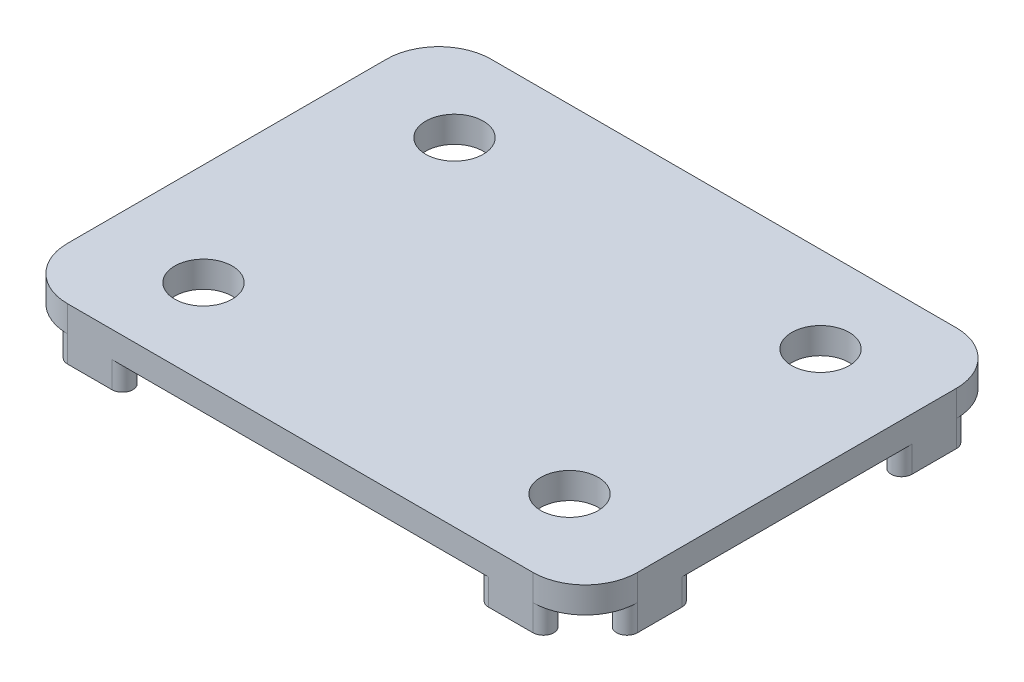
SolidWorks part; units mm, degrees
material "ABS"
ref_plane "Front Plane" through (0, 0, 0) normal (0, 0, 1) x (1, 0, 0)
ref_plane "Top Plane" through (0, 0, 0) normal (0, 1, 0) x (1, 0, 0)
ref_plane "Right Plane" through (0, 0, 0) normal (1, 0, 0) x (0, 0, -1)
sketch "Sketch1" plane through (0, 0, 0) normal (0, 1, 0) x (1, 0, 0)
  line L1 (-25.25, 18.25) -> (25.25, 18.25) construction
  line L2 (-25.25, 18.25) -> (-25.25, -18.25) construction
  line L3 (-25.25, -18.25) -> (25.25, -18.25) construction
  line L4 (25.25, 18.25) -> (25.25, -18.25) construction
  line L5 (-25.25, 18.25) -> (25.25, -18.25) construction
  line L6 (-25.25, -18.25) -> (25.25, 18.25) construction
  line L7 (27.25, -20.25) -> (-27.25, -20.25)
  line L8 (27.25, -20.25) -> (27.25, 20.25)
  line L9 (27.25, 20.25) -> (-27.25, 20.25)
  line L10 (-27.25, -20.25) -> (-27.25, 20.25)
  line L11 (27.25, -20.25) -> (-27.25, 20.25) construction
  line L12 (27.25, 20.25) -> (-27.25, -20.25) construction
  point P0 (0, 0)
  point P6 (0, 0)
  dimension "D1" = 36.5
  dimension "D2" = 50.5
  dimension "D3" = 2
  dimension "D4" = 2
extrude "Boss-Extrude1" add sketch "Sketch1" along normal blind 2.5
hole_wizard "M5 Clearance Hole1" positions "Sketch3" profile "Sketch4" hole size "M5" standard "ANSI Metric" end condition through all
sketch "Sketch3" plane through (0, 2.5, 0) normal (0, 1, 0) x (1, 0, 0)
  line L1 (-17.5, 12) -> (17.5, 12)
  line L2 (-17.5, 12) -> (-17.5, -12)
  line L3 (-17.5, -12) -> (17.5, -12)
  line L4 (17.5, 12) -> (17.5, -12)
  line L5 (-17.5, 12) -> (17.5, -12) construction
  line L6 (-17.5, -12) -> (17.5, 12) construction
  point P2 (17.5, -12)
  point P73 (-17.5, 12)
  point P74 (-17.5, -12)
  point P75 (17.5, 12)
  point P79 (0, 0)
  dimension "D1" = 24
  dimension "D2" = 35
sketch "Sketch4" plane through (17.5, 2.5, 12) normal (1, 0, 0) x (0, 0, 1)
  line L0 (0, 0) -> (0, 2.5)
  line L1 (0, 2.5) -> (2.75, 2.5)
  line L2 (2.75, 2.5) -> (2.75, 0)
  line L5 (2.75, 0) -> (0, 0)
  line L11 (0, -6.35) -> (0, 107.95) construction
  dimension "Thru Hole Dia." = 5.5
  dimension "Thru Hole Depth" = 2.5
fillet "Fillet1" radius 5 4 edges at (27.25, 1.25, -20.25) (27.25, 1.25, 20.25) (-27.25, 1.25, -20.25) (-27.25, 1.25, 20.25)
sketch "Sketch2" plane through (0, 0, 0) normal (0, 1, 0) x (1, 0, 0)
  line L0 (-25.25, 18.25) -> (-25.25, -18.25) construction
  line L1 (-25.25, 11) -> (-27.25, 11) construction
  line L2 (-25.25, 11) -> (-25.25, 15.25)
  line L3 (-25.25, 15.25) -> (-27.25, 15.25) construction
  line L4 (-27.25, 11) -> (-27.25, 15.25)
  line L5 (-27.25, -20.25) -> (-27.25, 20.25) construction
  line L6 (-25.25, 18.25) -> (25.25, 18.25) construction
  line L7 (-22.25, 18.25) -> (-18, 18.25)
  line L8 (-22.25, 18.25) -> (-22.25, 20.25) construction
  line L9 (-22.25, 20.25) -> (-18, 20.25)
  line L10 (-18, 18.25) -> (-18, 20.25) construction
  line L11 (27.25, 20.25) -> (-27.25, 20.25) construction
  arc A0 (-22.25, 18.25) -> (-22.25, 20.25) centre (-22.25, 19.25) cw
  arc A1 (-18, 18.25) -> (-18, 20.25) centre (-18, 19.25) ccw
  arc A2 (-27.25, 15.25) -> (-25.25, 15.25) centre (-26.25, 15.25) cw
  arc A3 (-27.25, 11) -> (-25.25, 11) centre (-26.25, 11) ccw
  dimension "D1" = 18
extrude "Boss-Extrude2" add sketch "Sketch2" against normal blind 2.5
mirror "Mirror1" about plane through (0, 0, 0) normal (0, 0, 1) of "Boss-Extrude2"
mirror "Mirror2" about plane through (0, 0, 0) normal (1, 0, 0) of "Mirror1", "Boss-Extrude2"
